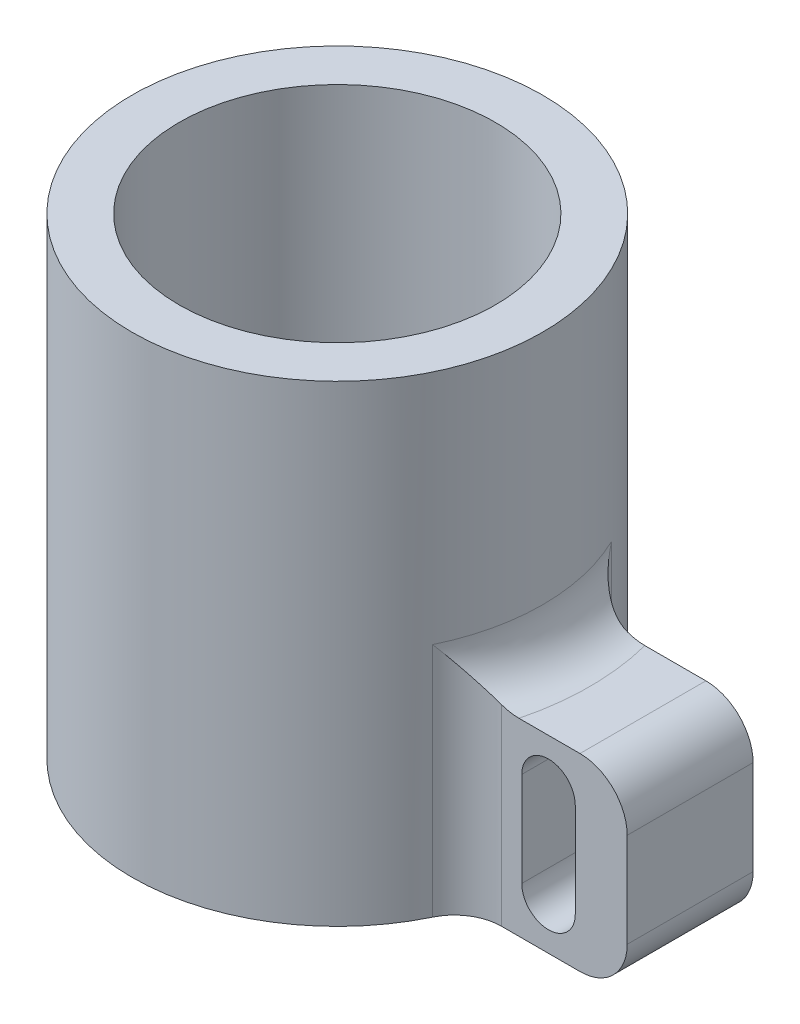
SolidWorks part; units mm, degrees
ref_plane "前视基准面" through (0, 0, 0) normal (0, 0, 1) x (1, 0, 0)
ref_plane "上视基准面" through (0, 0, 0) normal (0, 1, 0) x (1, 0, 0)
ref_plane "右视基准面" through (0, 0, 0) normal (1, 0, 0) x (0, 0, -1)
sketch "草图1" plane through (0, 0, 0) normal (0, 1, 0) x (1, 0, 0)
  circle A0 centre (0, 0) radius 10.05
  circle A1 centre (0, 0) radius 13.05
  dimension "D1" = 20.1
  dimension "D2" = 3
extrude "凸台-拉伸1" add sketch "草图1" along normal mid plane 30
sketch "草图2" plane through (0, 0, 0) normal (1, 0, 0) x (0, 0, -1)
  line L0 (0, 0) -> (0, -15) construction
  line L1 (-13.05, -15) -> (13.05, -15) construction
  line L3 (-4, -15) -> (4, -15)
  line L4 (-4, -15) -> (-4, -3)
  line L5 (-4, -3) -> (4, -3)
  line L6 (4, -15) -> (4, -3)
  dimension "D1" = 8
  dimension "D2" = 12
extrude "凸台-拉伸2" add sketch "草图2" along normal blind 10 from surface starting at face at (0, 15, 13.05)
sketch "草图4" plane through (0, -3, 0) normal (0, 1, 0) x (1, 0, 0)
  line L0 (22.4219, 4) -> (22.4219, -4)
  line L2 (22.4219, 4) -> (12.4219, 4)
  line L3 (12.4219, -4) -> (22.4219, -4)
  line L4 (22.4219, 4) -> (12.4219, 4)
  line L5 (12.4219, -4) -> (22.4219, -4)
  arc A2 (22.4219, -4) -> (22.4219, 4) centre (10, 0) ccw
  arc A3 (12.4219, -4) -> (12.4219, 4) centre (0, 0) ccw
  arc A4 (22.4219, -4) -> (22.4219, 4) centre (10, 0) ccw
  arc A5 (12.4219, -4) -> (12.4219, 4) centre (0, 0) ccw
  arc M5 (22.4219, -4) -> (22.4219, 4) centre (10, 0) ccw
  dimension "D1" = 0
extrude "切除-拉伸1" cut sketch "草图4" against normal through all contours L0 M5
sketch "草图5" plane through (0, 0, 4) normal (0, 0, 1) x (1, 0, 0)
  line L0 (17.4219, -15) -> (17.4219, -3) construction
  line L1 (12.4219, -15) -> (22.4219, -15) construction
  line L2 (12.4219, -3) -> (22.4219, -3) construction
  line L3 (22.4219, -3) -> (22.4219, -15) construction
  line L4 (17.4219, -12) -> (17.4219, -6) construction
  line L5 (15.7219, -12) -> (15.7219, -6)
  line L6 (19.1219, -12) -> (19.1219, -6)
  arc A0 (15.7219, -12) -> (19.1219, -12) centre (17.4219, -12) ccw
  arc A1 (19.1219, -6) -> (15.7219, -6) centre (17.4219, -6) ccw
  point P12 (17.4219, -9)
  dimension "D2" = 1.7
  dimension "D1" = 5
  dimension "D3" = 6
extrude "切除-拉伸2" cut sketch "草图5" against normal through all
fillet "圆角1" radius 3 2 edges at (22.4219, -15, 0) (22.4219, -3, 0)
fillet "圆角2" radius 3 3 edges at (12.4219, -9, -4) (13.05, -3, 0) (12.4219, -9, 4)
sketch "草图6" plane through (0, 0, 0) normal (1, 0, 0) x (0, 0, -1)
  circle A0 centre (0, 0) radius 1.75
  dimension "D1" = 3.5
extrude "切除-拉伸3" cut sketch "草图6" against normal through all
